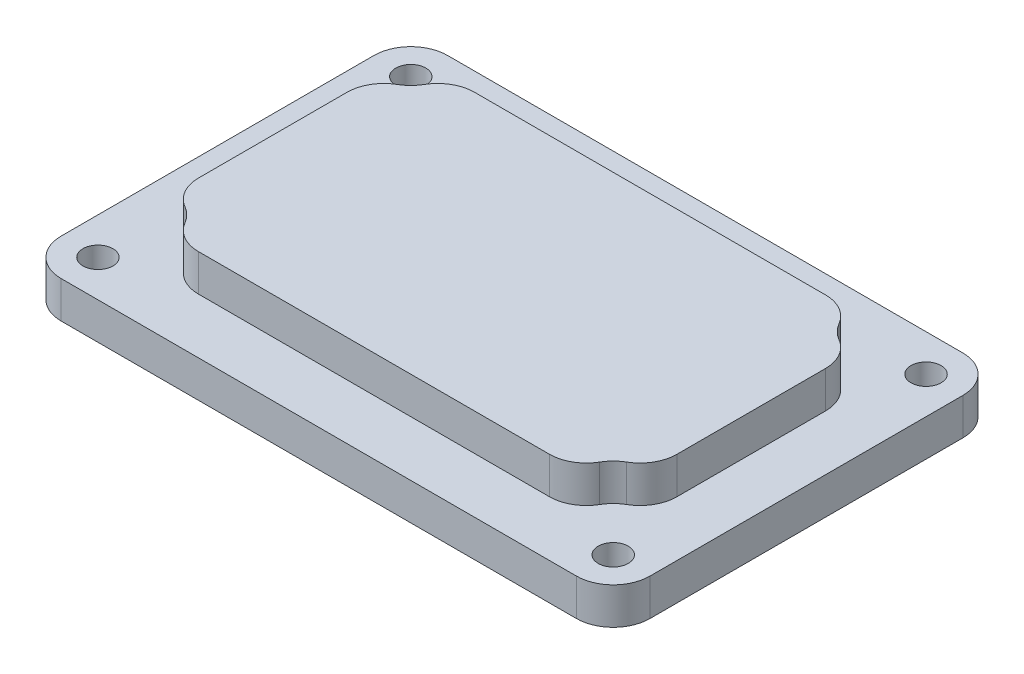
SolidWorks part; units mm, degrees
material "Cast Alloy Steel"
ref_plane "Front Plane" through (0, 0, 0) normal (0, 0, 1) x (1, 0, 0)
ref_plane "Top Plane" through (0, 0, 0) normal (0, 1, 0) x (1, 0, 0)
ref_plane "Right Plane" through (0, 0, 0) normal (1, 0, 0) x (0, 0, -1)
sketch "Sketch1" plane through (0, 0, 0) normal (0, 1, 0) x (1, 0, 0)
  line L1 (44.45, -33.3375) -> (-44.45, -33.3375)
  line L2 (50.8, -26.9875) -> (50.8, 26.9875)
  line L3 (44.45, 33.3375) -> (-44.45, 33.3375)
  line L4 (-50.8, -26.9875) -> (-50.8, 26.9875)
  line L5 (50.8, -33.3375) -> (-50.8, 33.3375) construction
  line L6 (50.8, 33.3375) -> (-50.8, -33.3375) construction
  arc A0 (50.8, 26.9875) -> (44.45, 33.3375) centre (44.45, 26.9875) ccw
  arc A1 (44.45, -33.3375) -> (50.8, -26.9875) centre (44.45, -26.9875) ccw
  arc A2 (-44.45, -33.3375) -> (-50.8, -26.9875) centre (-44.45, -26.9875) cw
  arc A3 (-44.45, 33.3375) -> (-50.8, 26.9875) centre (-44.45, 26.9875) ccw
  point P0 (0, 0)
  dimension "D3" = 6.35
  dimension "D1" = 101.6
  dimension "D2" = 66.675
extrude "Base Extrude" add sketch "Sketch1" along normal blind 6.35
sketch "Sketch2" plane through (0, 6.35, 0) normal (0, 1, 0) x (1, 0, 0)
  line L12 (41.275, 23.8125) -> (-41.275, 23.8125)
  line L13 (-41.275, 23.8125) -> (-41.275, -23.8125)
  line L14 (-41.275, -23.8125) -> (41.275, -23.8125)
  line L15 (41.275, -23.8125) -> (41.275, 23.8125)
  line L16 (41.275, 23.8125) -> (-41.275, 23.8125)
  line L17 (-41.275, 23.8125) -> (-41.275, -23.8125)
  line L18 (-41.275, -23.8125) -> (41.275, -23.8125)
  line L19 (41.275, -23.8125) -> (41.275, 23.8125)
  dimension "D1" = 9.525
extrude "Top Boss" add sketch "Sketch2" along normal blind 6.35 contours L16 L17 L18 L19
sketch "Sketch3" plane through (0, 12.7, 0) normal (0, 1, 0) x (1, 0, 0)
  line L0 (0, 0) -> (50.8, 0) construction
  line L1 (50.8, -26.9875) -> (50.8, 26.9875) construction
  line L2 (0, 0) -> (0, 33.3375) construction
  line L3 (44.45, 33.3375) -> (-44.45, 33.3375) construction
  circle A0 centre (41.275, 23.8125) radius 6.35
  circle A1 centre (-41.275, 23.8125) radius 6.35
  circle A2 centre (41.275, -23.8125) radius 6.35
  circle A3 centre (-41.275, -23.8125) radius 6.35
extrude "Base Cut" cut sketch "Sketch3" against normal up to surface (6.35 mm away) up to face at (0, 6.35, 0)
fillet "Fillet" radius 6.35 8 edges at (-41.275, 9.525, -17.4625) (-34.925, 9.525, -23.8125) (41.275, 9.525, -17.4625) (34.925, 9.525, -23.8125) (41.275, 9.525, 17.4625) (34.925, 9.525, 23.8125) (-34.925, 9.525, 23.8125) (-41.275, 9.525, 17.4625)
shell "Shell" thickness 3.175
sketch "Sketch4" plane through (0, 3.175, 0) normal (0, -1, 0) x (-1, 0, 0)
  line L0 (48.9401, -31.4776) -> (44.45, -26.9875)
  circle A4 centre (44.45, -26.9875) radius 6.35
  circle A5 centre (-44.45, -26.9875) radius 6.35
  circle A6 centre (-44.45, 26.9875) radius 6.35
  circle A7 centre (44.45, 26.9875) radius 6.35
  arc A8 (44.45, -33.3375) -> (50.8, -26.9875) centre (44.45, -26.9875) ccw construction
  point P5 (48.9401, -31.4776)
extrude "Corner Extrude" add sketch "Sketch4" along normal up to surface (3.175 mm away) contours A5 | A4 | A7 | A6 up to face at (0, 0, 0)
fillet "Shell Fillet" radius 0.7874 56 edges at (-39.9599, 0, 22.4974) (-39.9599, 3.175, 22.4974) (39.9599, 3.175, 22.4974) (39.9599, 0, 22.4974) (-39.9599, 0, -22.4974) (-39.9599, 3.175, -22.4974) (39.9599, 0, -22.4974) (39.9599, 3.175, -22.4974) (38.1, 3.175, 0) (0, 3.175, -20.6375) (-38.1, 3.175, 0) (0, 3.175, 20.6375) (-38.1, 9.525, 0) (0, 9.525, 20.6375) (38.1, 9.525, 0) (0, 9.525, -20.6375) (34.5398, 3.175, -17.0773) (34.5398, 9.525, -17.0773) (-34.5398, 9.525, 17.0773) (-34.5398, 3.175, 17.0773) (34.5398, 9.525, 17.0773) (34.5398, 3.175, 17.0773) (-34.5398, 9.525, -17.0773) (-34.5398, 3.175, -17.0773) (-37.6746, 3.175, -14.4015) (-37.6746, 9.525, -14.4015) (-31.864, 9.525, -20.2121) (-31.864, 3.175, -20.2121) (37.6746, 9.525, -14.4015) (37.6746, 3.175, -14.4015) (31.864, 3.175, -20.2121) (31.864, 9.525, -20.2121) (37.6746, 3.175, 14.4015) (37.6746, 9.525, 14.4015) (31.864, 9.525, 20.2121) (31.864, 3.175, 20.2121) (-31.864, 3.175, 20.2121) (-31.864, 9.525, 20.2121) (-37.6746, 9.525, 14.4015) (-37.6746, 3.175, 14.4015) (38.9507, 1.5875, 30.1625) (0, 3.175, 30.1625) (-38.9507, 1.5875, 30.1625) (0, 0, 30.1625) (-47.625, 1.5875, 21.4882) (-47.625, 3.175, 0) (-47.625, 1.5875, -21.4882) (-47.625, 0, 0) (47.625, 1.5875, 21.4882) (47.625, 0, 0) (47.625, 1.5875, -21.4882) (47.625, 3.175, 0) (-38.9507, 1.5875, -30.1625) (0, 3.175, -30.1625) (38.9507, 1.5875, -30.1625) (0, 0, -30.1625)
hole_wizard "#6 (0.204) Diameter Hole" positions "Sketch5" profile "Sketch6" hole size "#6" standard "ANSI Inch" end condition through all
sketch "Sketch5" plane through (0, 6.35, 0) normal (0, 1, 0) x (1, 0, 0)
  point P0 (-44.45, 26.9875)
  point P3 (44.45, 26.9875)
  point P6 (44.45, -26.9875)
  point P9 (-44.45, -26.9875)
sketch "Sketch6" plane through (-44.45, 6.35, -26.9875) normal (1, 0, 0) x (0, 0, 1)
  line L0 (0, 0) -> (0, 6.35)
  line L1 (0, 6.35) -> (2.5908, 6.35)
  line L2 (2.5908, 6.35) -> (2.5908, 0)
  line L5 (2.5908, 0) -> (0, 0)
  line L11 (0, -6.35) -> (0, 107.95) construction
  dimension "Thru Hole Dia." = 5.1816
  dimension "Thru Hole Depth" = 6.35
